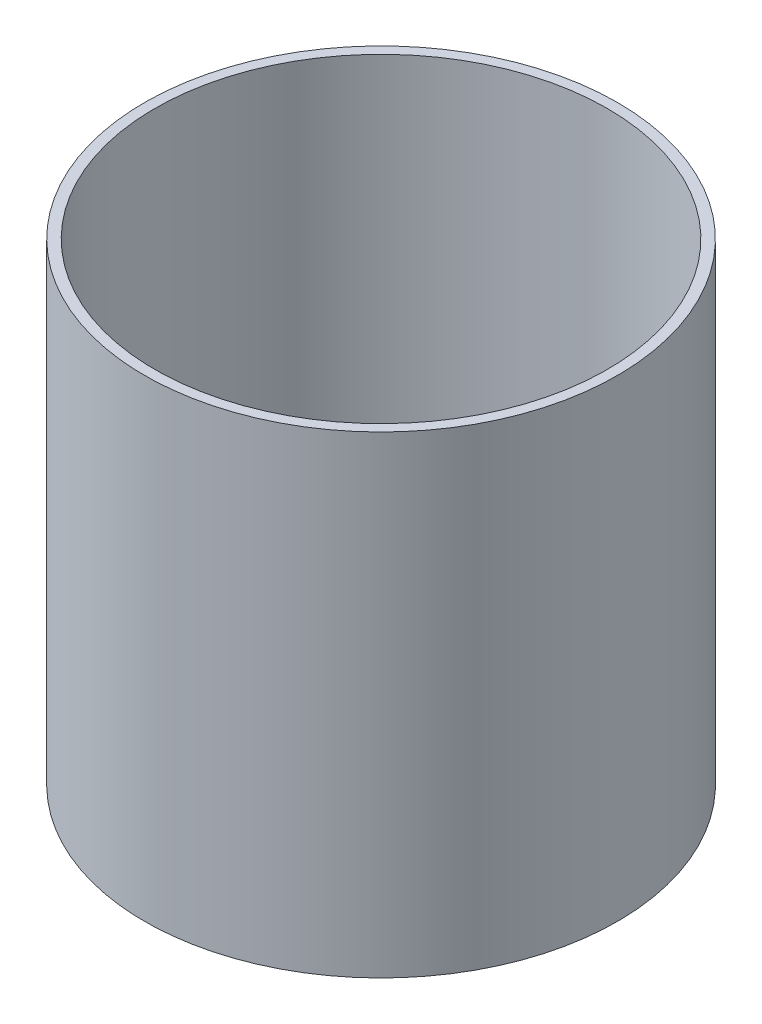
SolidWorks part; units mm, degrees
material "6061 Alloy"
ref_plane "Front Plane" through (0, 0, 0) normal (0, 0, 1) x (1, 0, 0)
ref_plane "Top Plane" through (0, 0, 0) normal (0, 1, 0) x (1, 0, 0)
ref_plane "Right Plane" through (0, 0, 0) normal (1, 0, 0) x (0, 0, -1)
sketch "Sketch1" plane through (0, 0, 0) normal (0, 1, 0) x (1, 0, 0)
  circle A0 centre (0, 0) radius 36.449
  circle A1 centre (0, 0) radius 38.1
  dimension "D1" = 72.898
  dimension "D2" = 76.2
extrude "Boss-Extrude1" add sketch "Sketch1" along normal blind 76.2
